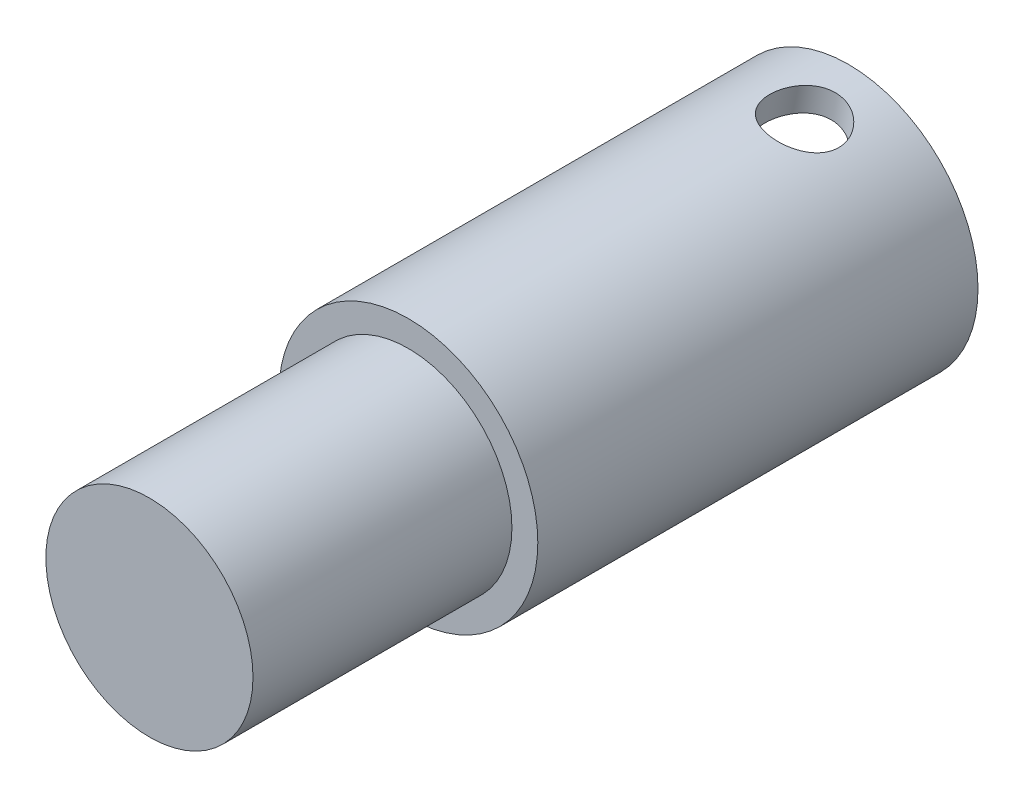
SolidWorks part; units mm, degrees
ref_plane "Front Plane" through (0, 0, 0) normal (0, 0, 1) x (1, 0, 0)
ref_plane "Top Plane" through (0, 0, 0) normal (0, 1, 0) x (1, 0, 0)
ref_plane "Right Plane" through (0, 0, 0) normal (1, 0, 0) x (0, 0, -1)
sketch "Sketch1" plane through (0, 0, 0) normal (0, 0, 1) x (1, 0, 0)
  line L1 (-5, 0) -> (5, 0) construction
  dimension "OD" = 10
sketch "Sketch2" plane through (0, 0, 0) normal (1, 0, 0) x (0, 0, -1)
  line L0 (13.5, 0) -> (-13.5, 0)
  point P4 (0, 0)
  dimension "Length" = 27
sketch "Sketch3" plane through (0, 0, 0) normal (0, 0, 1) x (1, 0, 0)
  circle A0 centre (0, 0) radius 5
extrude "Boss-Extrude1" add sketch "Sketch3" along normal up to vertex (13.5 mm away) and the other way up to vertex (13.5 mm away) up to point (0, 0, 13.5) other way up to point (0, 0, -13.5)
sketch "Sketch4" plane through (0, 0, 13.5) normal (0, 0, 1) x (1, 0, 0)
  circle A1 centre (0, 0) radius 4
  circle A2 centre (0, 0) radius 5 construction
  circle A3 centre (0, 0) radius 5
  dimension "D1" = 8
extrude "Cut-Extrude1" cut sketch "Sketch4" against normal blind 10
sketch "Sketch5" plane through (0, 0, -13.5) normal (0, 0, -1) x (-1, 0, 0)
  circle A0 centre (0, 0) radius 4
  dimension "D1" = 8
extrude "Cut-Extrude2" cut sketch "Sketch5" against normal blind 7.5
sketch "Sketch6" plane through (0, 0, -6) normal (0, 0, -1) x (-1, 0, 0)
  circle A0 centre (0, 0) radius 3.1
  dimension "D1" = 6.2
extrude "Cut-Extrude3" cut sketch "Sketch6" against normal blind 7
sketch "Sketch7" plane through (0, 0, 0) normal (0, 1, 0) x (1, 0, 0)
  line L0 (4, 13.5) -> (-4, 13.5) construction
  point P0 (0, 11)
  dimension "D1" = 2.5
ref_plane "Plane1" through (0, 0, -11) normal (0, 0, -1) x (-1, 0, 0)
hole_wizard "#6-32 Tapped Hole1" positions "3DSketch2" profile "Sketch11" tap size "#6-32" standard "ANSI Inch"
sketch3d "3DSketch2"
  point P0 (0.8177, 4.9327, -11)
sketch "Sketch11" plane through (0.8177, 4.9327, -11) normal (0, 0, 1) x (-0.9865, 0.1635, 0)
  line L0 (0, 0) -> (0, 1)
  line L1 (0, 1) -> (1.3525, 1)
  line L2 (1.3525, 1) -> (1.3525, 0)
  line L5 (1.3525, 0) -> (0, 0)
  line L11 (0, -6.35) -> (0, 107.95) construction
  dimension "Thru Tap Drill Dia." = 2.7051
  dimension "Thru Tap Drill Depth" = 1
cosmetic thread "Hole Thread1" parameters "D2"=3.5052
sketch "Sketch12" plane through (0, 0, -13.5) normal (0, 0, -1) x (-1, 0, 0)
  circle A0 centre (0, 0) radius 3
  dimension "D1" = 6
extrude "Cut-Extrude4" [suppressed] cut sketch "Sketch12" against normal blind 12
sketch "Sketch13" [suppressed] plane through (0, 0, 0) normal (0, 1, 0) x (1, 0, 0)
  line L0 (3, 13.5) -> (-3, 13.5) construction
  point P0 (0, 11)
  dimension "D1" = 2.5
ref_plane "Plane2" [suppressed] through (0, 0, -11) normal (0, 0, -1) x (-1, 0, 0)
hole_wizard "#6-32 Tapped Hole2" [suppressed] positions "3DSketch3" profile "Sketch14" tap size "#6-32" standard "ANSI Inch"
sketch3d "3DSketch3" [suppressed]
  point P0 (0.2365, 4.9944, -11)
sketch "Sketch14" plane through (0.2365, 4.9944, -11) normal (0, 0, 1) x (-0.9989, 0.0473, 0)
  line L0 (0, 0) -> (0, 2)
  line L1 (0, 2) -> (1.3525, 2)
  line L2 (1.3525, 2) -> (1.3525, 0)
  line L5 (1.3525, 0) -> (0, 0)
  line L11 (0, -6.35) -> (0, 107.95) construction
  dimension "Thru Tap Drill Dia." = 2.7051
  dimension "Thru Tap Drill Depth" = 2
